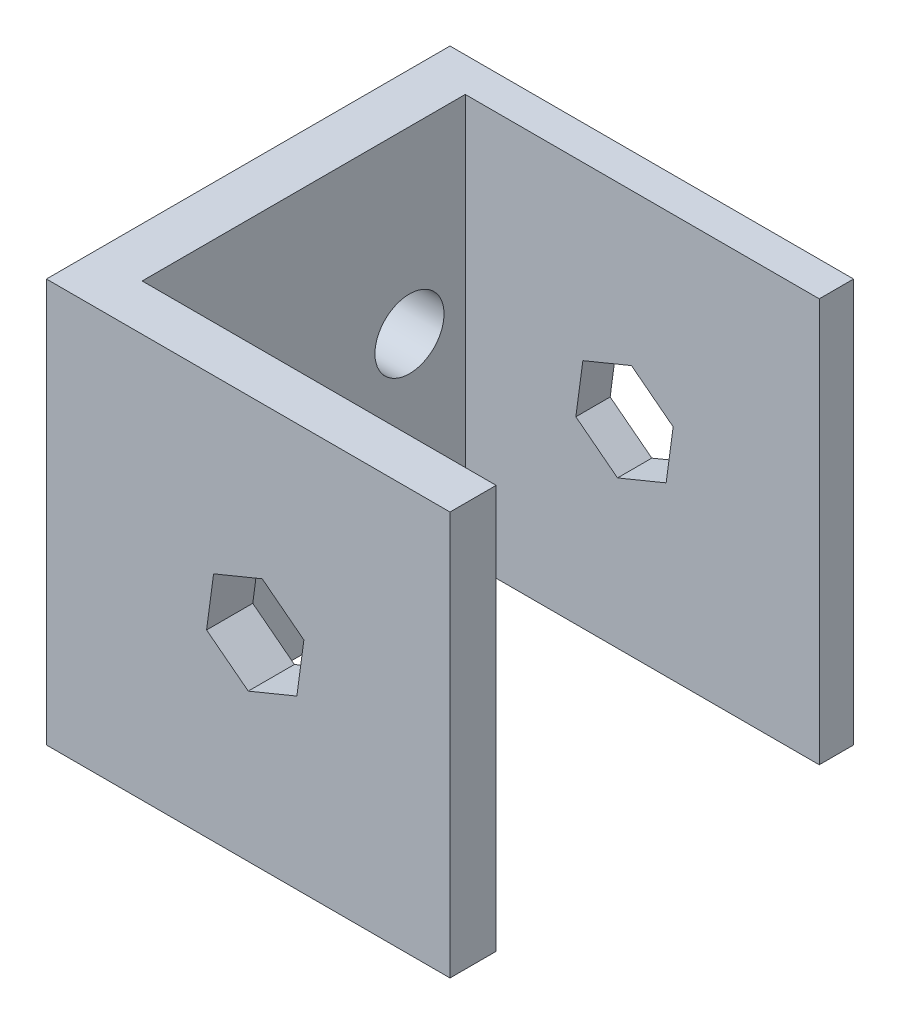
SolidWorks part; units mm, degrees
ref_plane "Front" through (0, 0, 0) normal (0, 0, 1) x (1, 0, 0)
ref_plane "Top" through (0, 0, 0) normal (0, 1, 0) x (1, 0, 0)
ref_plane "Right" through (0, 0, 0) normal (1, 0, 0) x (0, 0, -1)
sketch "Sketch1" plane through (0, 0, 0) normal (0, 1, 0) x (1, 0, 0)
  line L1 (0, 0) -> (100, 0)
  line L2 (0, 0) -> (0, 100)
  line L3 (0, 100) -> (100, 100)
  line L4 (100, 0) -> (100, 100)
  dimension "D1" = 100
  dimension "D2" = 100
extrude "Boss-Extrude1" add sketch "Sketch1" along normal blind 100
sketch "Sketch2" plane through (0, 100, 0) normal (0, 1, 0) x (1, 0, 0)
  line L0 (100, 0) -> (100, 100) construction
  line L1 (12.2825, 11.4381) -> (100, 11.4381)
  line L2 (12.2825, 11.4381) -> (12.2825, 91.4995)
  line L3 (12.2825, 91.4995) -> (100, 91.4995)
  line L4 (100, 11.4381) -> (100, 91.4995)
extrude "Cut-Extrude1" cut sketch "Sketch2" against normal blind 100
sketch "Sketch3" plane through (0, 0, -100) normal (0, 0, -1) x (-1, 0, 0)
  line L1 (-39.6865, 44.525) -> (-41.4168, 57.4419)
  line L2 (-41.4168, 57.4419) -> (-53.4683, 62.4019)
  line L3 (-53.4683, 62.4019) -> (-63.7895, 54.445)
  line L4 (-63.7895, 54.445) -> (-62.0593, 41.5281)
  line L5 (-62.0593, 41.5281) -> (-50.0078, 36.5681)
  line L6 (-50.0078, 36.5681) -> (-39.6865, 44.525)
  circle A0 centre (-51.738, 49.485) radius 11.2863 construction
extrude "Cut-Extrude2" cut sketch "Sketch3" against normal blind 110
sketch "Sketch4" plane through (0, 0, 0) normal (-1, 0, 0) x (0, 0, 1)
  line L0 (-50, 0) -> (-50, 100)
  line L1 (-100, 0) -> (0, 0) construction
  line L2 (-100, 100) -> (0, 100) construction
  circle A0 centre (-22.3211, 55.5406) radius 8.5618
  circle A1 centre (-77.6789, 55.5406) radius 8.5618
extrude "Cut-Extrude3" cut sketch "Sketch4" against normal blind 110 contours A1 | A0
